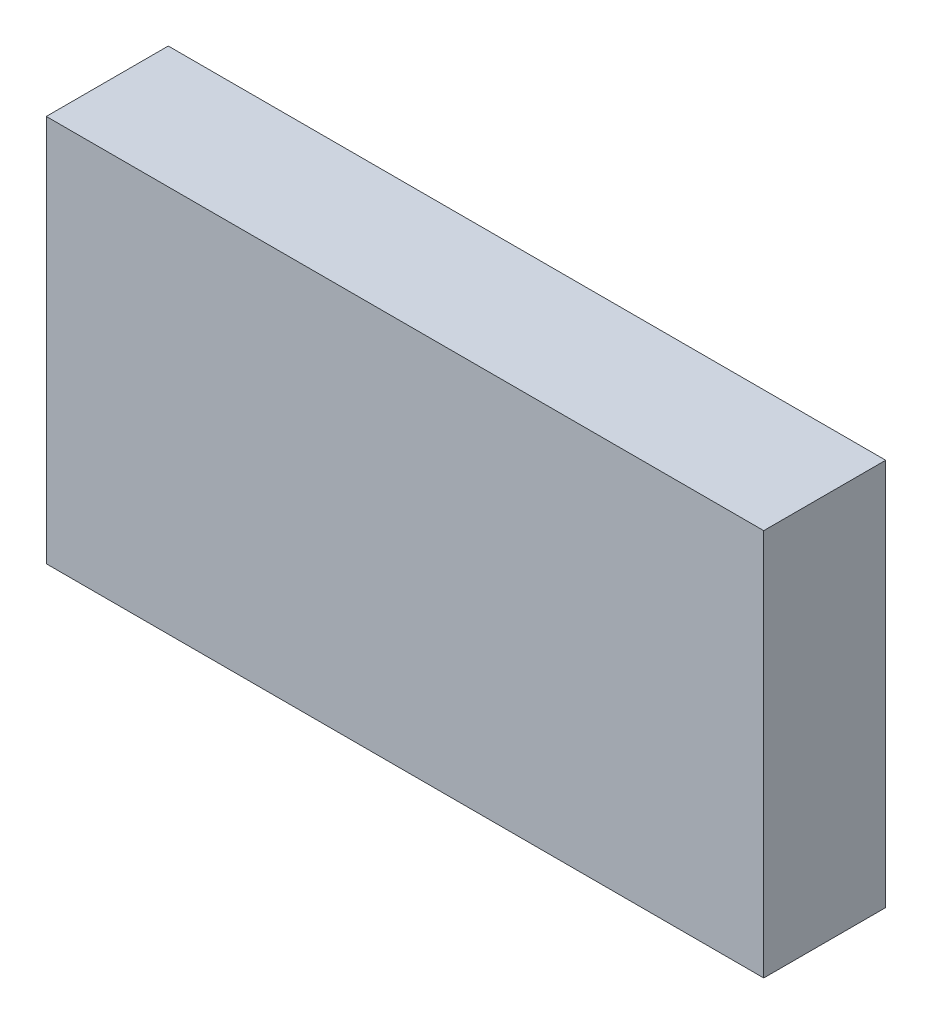
SolidWorks part; units mm, degrees
ref_plane "前视基准面" through (0, 0, 0) normal (0, 0, 1) x (1, 0, 0)
ref_plane "上视基准面" through (0, 0, 0) normal (0, 1, 0) x (1, 0, 0)
ref_plane "右视基准面" through (0, 0, 0) normal (1, 0, 0) x (0, 0, -1)
other "Configuration Table"
sketch "草图1" plane through (0, 0, 0) normal (0, 0, 1) x (1, 0, 0)
  line L1 (52.8434, -10.4815) -> (-47.1566, -10.4815)
  line L2 (52.8434, -10.4815) -> (52.8434, 43.5185)
  line L3 (52.8434, 43.5185) -> (-47.1566, 43.5185)
  line L4 (-47.1566, -10.4815) -> (-47.1566, 43.5185)
  dimension "D1" = 54
  dimension "D2" = 100
extrude "凸台-拉伸1" add sketch "草图1" along normal blind 17
